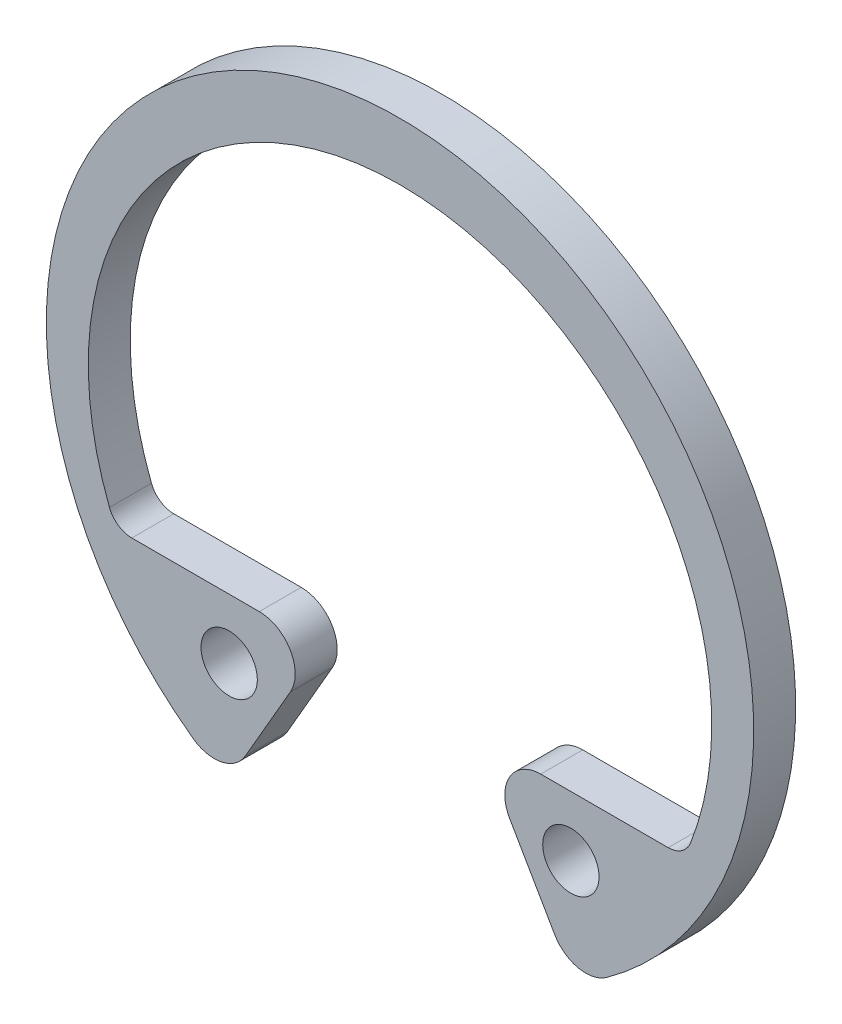
SolidWorks part; units mm, degrees
material "Alloy Steel"
ref_plane "Front" through (0, 0, 0) normal (0, 0, 1) x (1, 0, 0)
ref_plane "Top" through (0, 0, 0) normal (0, 1, 0) x (1, 0, 0)
ref_plane "Right" through (0, 0, 0) normal (1, 0, 0) x (0, 0, -1)
sketch "Sketch1" plane through (0, 0, 0) normal (0, 0, 1) x (1, 0, 0)
  line L0 (-5.6814, -3.048) -> (-2.9817, -3.048)
  line L1 (-2.3218, -4.191) -> (-3.275, -5.842)
  line L2 (0, 0) -> (0, -5.4107) construction
  line L3 (2.3218, -4.191) -> (3.275, -5.842)
  line L4 (5.6814, -3.048) -> (2.9817, -3.048)
  arc A0 (4.3804, -6.0792) -> (-4.3804, -6.0792) centre (0, 0) ccw
  arc A1 (6.1548, -2.7241) -> (-6.1548, -2.7241) centre (0, -0.3302) ccw
  arc A2 (3.275, -5.842) -> (4.3804, -6.0792) centre (3.935, -5.461) ccw
  arc A3 (-3.275, -5.842) -> (-4.3804, -6.0792) centre (-3.935, -5.461) cw
  arc A4 (2.3218, -4.191) -> (2.9817, -3.048) centre (2.9817, -3.81) cw
  arc A5 (-2.9817, -3.048) -> (-2.3218, -4.191) centre (-2.9817, -3.81) cw
  circle A6 centre (-3.6195, -4.318) radius 0.5969
  circle A7 centre (3.6195, -4.318) radius 0.5969
  arc A8 (5.6814, -3.048) -> (6.1548, -2.7241) centre (5.6814, -2.54) ccw
  arc A9 (-5.6814, -3.048) -> (-6.1548, -2.7241) centre (-5.6814, -2.54) cw
  point P12 (3.6729, -6.5311)
  point P15 (-3.6729, -6.5311)
  point P18 (1.6619, -3.048)
  point P21 (-1.6619, -3.048)
  point P28 (6.0188, -3.048)
  point P31 (-6.0188, -3.048)
  dimension "D1" = 14.986
  dimension "D2" = 13.208
  dimension "D5" = 0.762
  dimension "D8" = 7.239
  dimension "D9" = 1.1938
  dimension "D10" = 0.508
  dimension "D3" = 0.3302
  dimension "D4" = 60
  dimension "D6" = 1.651
  dimension "D7" = 4.318
  dimension "D11" = 3.048
extrude "Boss-Extrude1" add sketch "Sketch1" along normal blind 0.889
